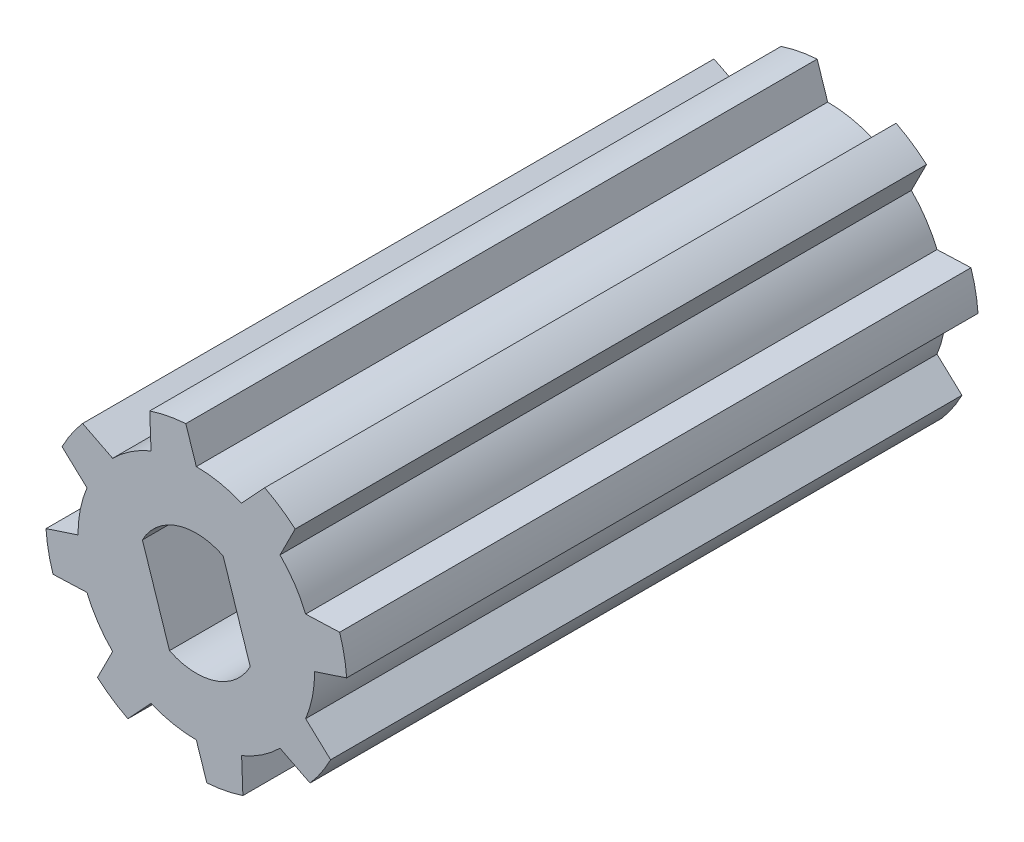
SolidWorks part; units mm, degrees
ref_plane "Front Plane" through (0, 0, 0) normal (0, 0, 1) x (1, 0, 0)
ref_plane "Top Plane" through (0, 0, 0) normal (0, 1, 0) x (1, 0, 0)
ref_plane "Right Plane" through (0, 0, 0) normal (1, 0, 0) x (0, 0, -1)
ref_plane "Plane1" through (0, 0, 26) normal (0, 0, 1) x (1, 0, 0)
sketch "Sketch1" plane through (0, 0, 26) normal (0, 0, 1) x (1, 0, 0)
  line L0 (4.8737, 0) -> (6.1903, 0.4329)
  line L1 (5.9017, 1.9176) -> (4.5027, 1.8651)
  line L2 (3.4462, 3.4462) -> (4.0711, 4.6833)
  line L3 (2.8172, 5.529) -> (1.8651, 4.5027)
  line L4 (0, 4.8737) -> (-0.4329, 6.1903)
  line L5 (-1.9176, 5.9017) -> (-1.8651, 4.5027)
  line L6 (-3.4462, 3.4462) -> (-4.6833, 4.0711)
  line L7 (-5.529, 2.8172) -> (-4.5027, 1.8651)
  line L8 (-4.8737, 0) -> (-6.1903, -0.4329)
  line L9 (-5.9017, -1.9176) -> (-4.5027, -1.8651)
  line L10 (-3.4462, -3.4462) -> (-4.0711, -4.6833)
  line L11 (-2.8172, -5.529) -> (-1.8651, -4.5027)
  line L12 (0, -4.8737) -> (0.4329, -6.1903)
  line L13 (1.9176, -5.9017) -> (1.8651, -4.5027)
  line L14 (3.4462, -3.4462) -> (4.6833, -4.0711)
  line L15 (5.529, -2.8172) -> (4.5027, -1.8651)
  line L16 (1.1048, 2.2426) -> (2.2201, -1.1495)
  line L17 (-1.1048, -2.2426) -> (-2.2201, 1.1495)
  arc A0 (4.5027, -1.8651) -> (4.8737, 0) centre (0, 0) ccw
  arc A1 (6.1903, 0.4329) -> (5.9017, 1.9176) centre (0, 0) ccw
  arc A2 (4.5027, 1.8651) -> (3.4462, 3.4462) centre (0, 0) ccw
  arc A3 (4.0711, 4.6833) -> (2.8172, 5.529) centre (0, 0) ccw
  arc A4 (1.8651, 4.5027) -> (0, 4.8737) centre (0, 0) ccw
  arc A5 (-0.4329, 6.1903) -> (-1.9176, 5.9017) centre (0, 0) ccw
  arc A6 (-1.8651, 4.5027) -> (-3.4462, 3.4462) centre (0, 0) ccw
  arc A7 (-4.6833, 4.0711) -> (-5.529, 2.8172) centre (0, 0) ccw
  arc A8 (-4.5027, 1.8651) -> (-4.8737, 0) centre (0, 0) ccw
  arc A9 (-6.1903, -0.4329) -> (-5.9017, -1.9176) centre (0, 0) ccw
  arc A10 (-4.5027, -1.8651) -> (-3.4462, -3.4462) centre (0, 0) ccw
  arc A11 (-4.0711, -4.6833) -> (-2.8172, -5.529) centre (0, 0) ccw
  arc A12 (-1.8651, -4.5027) -> (0, -4.8737) centre (0, 0) ccw
  arc A13 (0.4329, -6.1903) -> (1.9176, -5.9017) centre (0, 0) ccw
  arc A14 (1.8651, -4.5027) -> (3.4462, -3.4462) centre (0, 0) ccw
  arc A15 (4.6833, -4.0711) -> (5.529, -2.8172) centre (0, 0) ccw
  arc A16 (-2.2201, 1.1495) -> (1.1048, 2.2426) centre (0, 0) cw
  arc A17 (2.2201, -1.1495) -> (-1.1048, -2.2426) centre (0, 0) cw
extrude "Boss-Extrude1" add sketch "Sketch1" against normal blind 26
